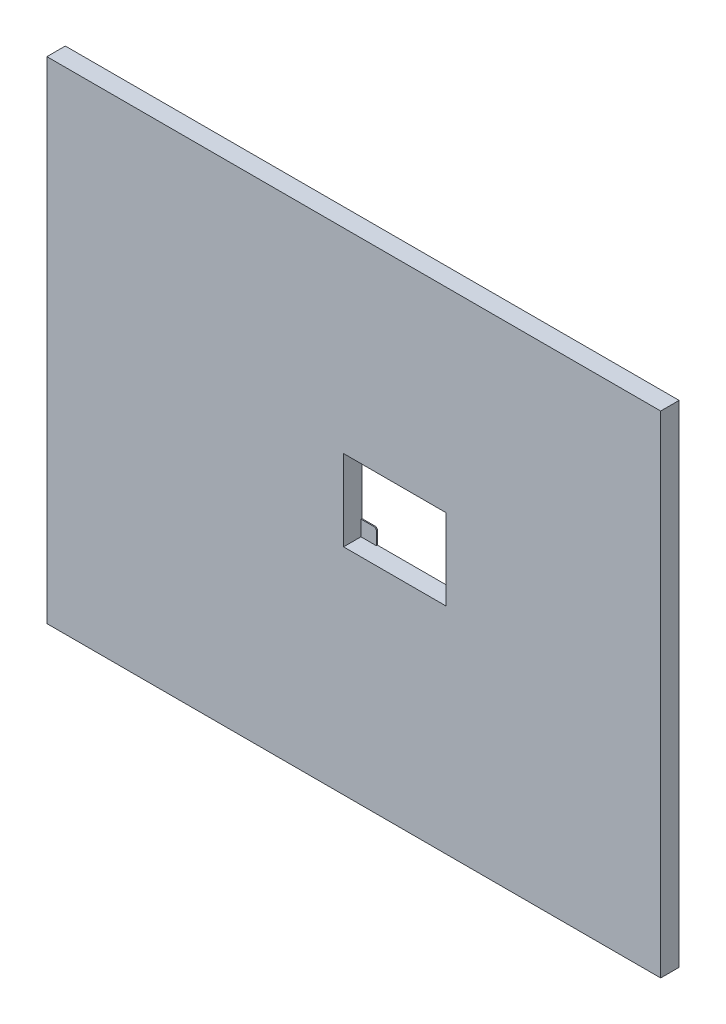
SolidWorks part; units mm, degrees
ref_plane "Plan de face" through (0, 0, 0) normal (0, 0, 1) x (1, 0, 0)
ref_plane "Plan de dessus" through (0, 0, 0) normal (0, 1, 0) x (1, 0, 0)
ref_plane "Plan de droite" through (0, 0, 0) normal (1, 0, 0) x (0, 0, -1)
sketch "Esquisse1" plane through (0, 0, 0) normal (0, 0, 1) x (1, 0, 0)
  line L1 (-300, 240) -> (300, 240)
  line L2 (-300, 240) -> (-300, -240)
  line L3 (-300, -240) -> (300, -240)
  line L4 (300, 240) -> (300, -240)
  line L5 (-300, 240) -> (300, -240) construction
  line L6 (-300, -240) -> (300, 240) construction
  point P0 (0, 0)
  dimension "D1" = 600
  dimension "D2" = 480
extrude "Boss.-Extru.1" add sketch "Esquisse1" along normal blind 18
sketch "Esquisse2" plane through (0, 0, 18) normal (0, 0, 1) x (1, 0, 0)
  line L0 (300, -240) -> (300, 240) construction
  line L1 (-10, -30) -> (90, -30)
  line L2 (-10, -30) -> (-10, 49)
  line L3 (-10, 49) -> (90, 49)
  line L4 (90, -30) -> (90, 49)
  line L5 (-300, -240) -> (300, -240) construction
  dimension "D1" = 210
  dimension "D2" = 210
  dimension "D3" = 100
  dimension "D4" = 79
extrude "Enlèv. mat.-Extru.1" cut sketch "Esquisse2" against normal blind 17
sketch "Esquisse4" plane through (0, 0, 1) normal (0, 0, 1) x (1, 0, 0)
  line L1 (-10, 49) -> (5, 49)
  line L2 (-10, 49) -> (-10, 34)
  line L3 (-10, 34) -> (5, 34)
  line L4 (5, 49) -> (5, 34)
  line L5 (90, 49) -> (75, 49)
  line L6 (90, 49) -> (90, 34)
  line L7 (90, 34) -> (75, 34)
  line L8 (75, 49) -> (75, 34)
  line L9 (90, -30) -> (75, -30)
  line L10 (90, -30) -> (90, -15)
  line L11 (90, -15) -> (75, -15)
  line L12 (75, -30) -> (75, -15)
  line L13 (-10, -30) -> (5, -30)
  line L14 (-10, -30) -> (-10, -15)
  line L15 (-10, -15) -> (5, -15)
  line L16 (5, -30) -> (5, -15)
  line L17 (-10, 49) -> (90, 49)
  line L18 (-10, 49) -> (-10, -30)
  line L19 (-10, -30) -> (90, -30)
  line L20 (90, 49) -> (90, -30)
  line M13 (-10, 49) -> (-10, -30)
  line M14 (-10, -30) -> (90, -30)
  line M15 (90, -30) -> (90, 49)
  line M16 (90, 49) -> (-10, 49)
  dimension "D1" = 15
  dimension "D2" = 15
  dimension "D3" = 15
  dimension "D4" = 15
  dimension "D5" = 15
  dimension "D6" = 15
  dimension "D7" = 15
  dimension "D8" = 15
extrude "Enlèv. mat.-Extru.3" cut sketch "Esquisse4" against normal blind 10 contours L16 L12 L11 L7 L8 L4 L3 L15 M14 M15 M16 M13
fillet "Congé1" radius 2 4 edges at (75, 34, 0.5) (5, 34, 0.5) (5, -15, 0.5) (75, -15, 0.5)
